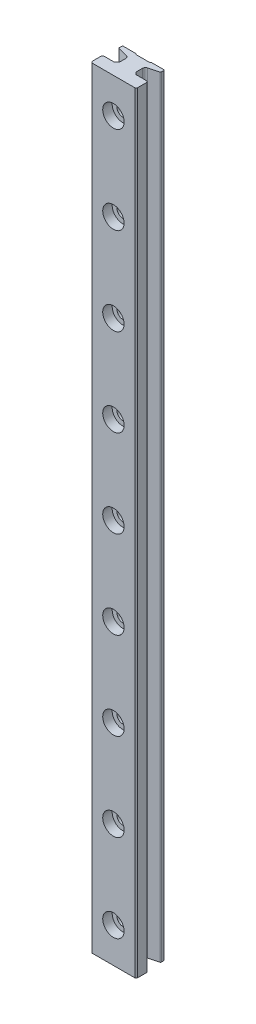
SolidWorks part; units mm, degrees
ref_plane "Front Plane" through (0, 0, 0) normal (0, 0, 1) x (1, 0, 0)
ref_plane "Top Plane" through (0, 0, 0) normal (0, 1, 0) x (1, 0, 0)
ref_plane "Right Plane" through (0, 0, 0) normal (1, 0, 0) x (0, 0, -1)
ref_plane "Ebene1" through (0, 25, 0) normal (0, 1, 0) x (1, 0, 0)
sketch "Skizze1" plane through (0, 25, 0) normal (0, 1, 0) x (1, 0, 0)
  line L0 (1.96, -0.24) -> (-1.96, -0.24)
  line L1 (-1.96, -0.24) -> (-1.96, 0)
  line L2 (-1.96, 0) -> (-5.84, 0)
  line L3 (-6, -0.16) -> (-6, -0.9465)
  line L4 (-5.8518, -1.1397) -> (-2.9929, -1.9057)
  line L5 (-2.4, -2.6785) -> (-2.4, -4.5)
  line L6 (-2.4, -4.5) -> (-3.1, -5.2)
  line L7 (-3.1, -5.2) -> (-6.2, -5.2)
  line L8 (-6.2, -5.2) -> (-6.5, -5.5)
  line L9 (-6.5, -5.5) -> (-6.5, -8.28)
  line L10 (-6.5, -8.28) -> (-6.18, -8.6)
  line L11 (-6.18, -8.6) -> (6.18, -8.6)
  line L12 (6.18, -8.6) -> (6.5, -8.28)
  line L13 (6.5, -8.28) -> (6.5, -5.5)
  line L14 (6.5, -5.5) -> (6.2, -5.2)
  line L15 (6.2, -5.2) -> (3.1, -5.2)
  line L16 (3.1, -5.2) -> (2.4, -4.5)
  line L17 (2.4, -4.5) -> (2.4, -2.6785)
  line L18 (2.9929, -1.9057) -> (5.8518, -1.1397)
  line L19 (6, -0.9465) -> (6, -0.16)
  line L20 (5.84, 0) -> (1.96, 0)
  line L21 (1.96, 0) -> (1.96, -0.24)
  arc A0 (-5.84, 0) -> (-6, -0.16) centre (-5.84, -0.16) ccw
  arc A1 (-6, -0.9465) -> (-5.8518, -1.1397) centre (-5.8, -0.9465) ccw
  arc A2 (-2.9929, -1.9057) -> (-2.4, -2.6785) centre (-3.2, -2.6785) cw
  arc A3 (2.4, -2.6785) -> (2.9929, -1.9057) centre (3.2, -2.6785) cw
  arc A4 (5.8518, -1.1397) -> (6, -0.9465) centre (5.8, -0.9465) ccw
  arc A5 (6, -0.16) -> (5.84, 0) centre (5.84, -0.16) ccw
extrude "Aufsatz-Linear austragen1" add sketch "Skizze1" against normal blind 220
hole_wizard "Stirnsenkung für M3 Sechskantschraube, Gewinde bis Kopf1" positions "Skizze3" profile "Skizze2" counterbore size "M3" standard "ANSI Metrisch" end condition through all
sketch "Skizze3" plane through (0, 0, 8.6) normal (0, 0, 1) x (1, 0, 0)
  line L4 (-6.18, -85) -> (6.18, -85) construction
  line L5 (-6.18, -195) -> (-6.18, 25) construction
  line L6 (6.18, -195) -> (6.18, 25) construction
  point P0 (0, -85)
  point P77 (0, -60)
  point P78 (0, -35)
  point P79 (0, -10)
  point P80 (0, 15)
  point P81 (0, -85)
  point P82 (0, -60)
  point P83 (0, -35)
  point P84 (0, -10)
  point P85 (0, -110)
  point P86 (0, -85)
  point P87 (0, -60)
  point P88 (0, -35)
  point P89 (0, -135)
  point P90 (0, -110)
  point P91 (0, -85)
  point P92 (0, -60)
  point P93 (0, -160)
  point P94 (0, -135)
  point P95 (0, -110)
  point P96 (0, -85)
  point P97 (0, -110)
  point P98 (0, -135)
  point P99 (0, -160)
  point P100 (0, -185)
  dimension "D1" = 5
  dimension "D2" = 5
sketch "Skizze2" plane through (0, -85, 8.6) normal (1, 0, 0) x (0, -1, 0)
  line L0 (0, 0) -> (0, 8.6)
  line L1 (0, 8.6) -> (1.7, 8.6)
  line L3 (1.7, 8.6) -> (1.7, 2.7)
  line L4 (1.7, 2.7) -> (3.05, 2.7)
  line L5 (3.05, 2.7) -> (3.05, 0)
  line L7 (3.05, 0) -> (0, 0)
  line L11 (0, -6.35) -> (0, 107.95) construction
  dimension "Bohrerdurchmesser" = 3.4
  dimension "Bohrungstiefe" = 8.6
  dimension "Senkdurchmesser2" = 6.1
  dimension "Senktiefe2" = 2.7
draft "Formschräge1" type of draft neutral plane draft angle 45 faces to draft 2 face at (-1.96, -85, 0.12) face at (1.96, -85, 0.12) neutral plane through (1.96, -195, 0.24) neutral plane normal (0, 0, -1) parameters "D1"=45
